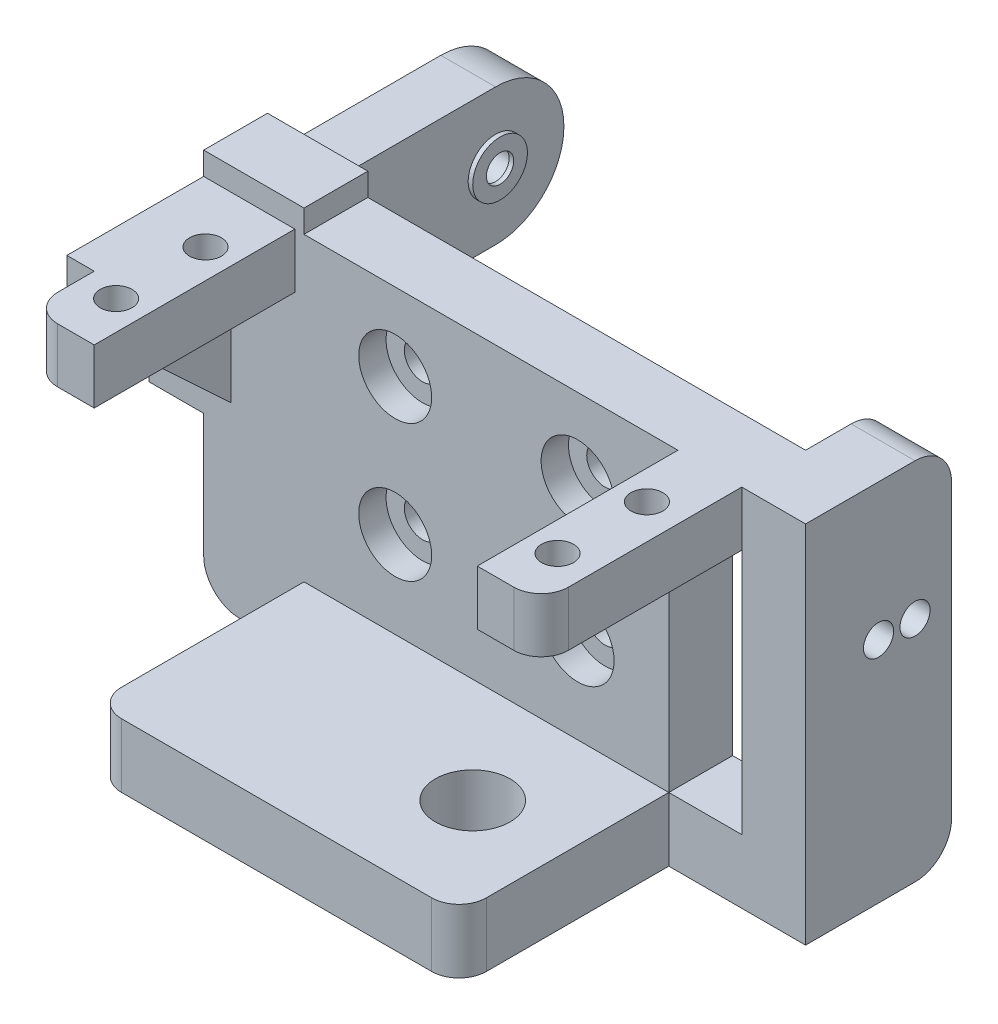
SolidWorks part; units mm, degrees
ref_plane "前视基准面" through (0, 0, 0) normal (0, 0, 1) x (1, 0, 0)
ref_plane "上视基准面" through (0, 0, 0) normal (0, 1, 0) x (1, 0, 0)
ref_plane "右视基准面" through (0, 0, 0) normal (1, 0, 0) x (0, 0, -1)
sketch "草图4" plane through (0, 0, 0) normal (0, 1, 0) x (1, 0, 0)
  line L0 (0, 17.6534) -> (0, -5.833) construction
  line L2 (-28, 28.5) -> (28, 28.5)
  line L3 (-28, 28.5) -> (-28, 2.5)
  line L4 (-25, -0.5) -> (-21, -0.5)
  line L5 (28, 28.5) -> (28, 2.5)
  line L6 (-28, 28.5) -> (28, -0.5) construction
  line L7 (-28, -0.5) -> (28, 28.5) construction
  line L8 (-21, 21.5) -> (21, 21.5)
  line L9 (-21, 21.5) -> (-21, -0.5)
  line L11 (21, 21.5) -> (21, -0.5)
  line L12 (-21, 21.5) -> (21, -0.5) construction
  line L13 (-21, -0.5) -> (21, 21.5) construction
  line L14 (21, -0.5) -> (25, -0.5)
  line L15 (20, 20) -> (-20, 20) construction
  circle A0 centre (-24.2, 14.9) radius 1.75
  circle A1 centre (-24.2, 5.1) radius 1.75
  circle A2 centre (24.2, 14.9) radius 1.75
  circle A3 centre (24.2, 5.1) radius 1.75
  arc A4 (25, -0.5) -> (28, 2.5) centre (25, 2.5) ccw
  arc A5 (-25, -0.5) -> (-28, 2.5) centre (-25, 2.5) cw
  point P3 (0, 14)
  point P8 (0, 10.5)
  dimension "D6" = 3.5
  dimension "D7" = 3.5
  dimension "D8" = 3.5
  dimension "D9" = 3.5
  dimension "D10" = 3
  dimension "D1" = 22
  dimension "D2" = 1.5
  dimension "D3" = 7
  dimension "D4" = 42
  dimension "D5" = 7
extrude "凸台-拉伸1" add sketch "草图4" against normal blind 6 from surface
sketch "草图5" plane through (0, 0, -28.5) normal (0, 0, -1) x (-1, 0, 0)
  line L0 (0, 4.5795) -> (0, 37.3232) construction
  line L1 (-28, 24.2) -> (28, 24.2) construction
  line L2 (-20, 24.2) -> (20, 24.2)
  line L3 (-20, 24.2) -> (-20, -9.8)
  line L4 (-20, -9.8) -> (20, -9.8)
  line L5 (20, 24.2) -> (20, -9.8)
  line L6 (-20, 24.2) -> (20, -9.8) construction
  line L7 (-20, -9.8) -> (20, 24.2) construction
  line L8 (-20, 14.2) -> (20, 14.2) construction
  circle A0 centre (-10, 21.7) radius 2
  circle A1 centre (10, 21.7) radius 2
  circle A4 centre (10, 6.7) radius 2
  circle A5 centre (-10, 6.7) radius 2
  point P3 (0, 7.2)
  dimension "D3" = 4
  dimension "D1" = 40
  dimension "D2" = 34
  dimension "D4" = 20
  dimension "D6" = 10
  dimension "D7" = 15
extrude "凸台-拉伸2" add sketch "草图5" against normal blind 7
sketch "草图6" plane through (0, 0, 0) normal (0, 0, 1) x (1, 0, 0)
  circle A0 centre (-10, 21.7) radius 4
  circle A1 centre (10, 21.7) radius 4
  circle A5 centre (-10, 6.7) radius 4
  circle A6 centre (10, 6.7) radius 4
  dimension "D1" = 8
extrude "切除-拉伸1" cut sketch "草图6" against normal blind 3 from surface at -21.5 starting at face at (0, 17.2, -21.5)
sketch "草图7" plane through (0, 0, 0) normal (0, 1, 0) x (1, 0, 0)
  line L0 (-20, 21.5) -> (-20, 28.5) construction
  line L1 (20, 21.5) -> (-20, 21.5)
  line L2 (20, 21.5) -> (20, 1.5)
  line L3 (17, -1.5) -> (-17, -1.5)
  line L4 (-20, 21.5) -> (-20, 1.5)
  circle A0 centre (10, 10) radius 4.1
  arc A1 (-17, -1.5) -> (-20, 1.5) centre (-17, 1.5) cw
  arc A2 (17, -1.5) -> (20, 1.5) centre (17, 1.5) ccw
  point P14 (20, -1.5)
  dimension "D1" = 8.2
  dimension "D3" = 3
  dimension "D2" = 23
extrude "凸台-拉伸3" add sketch "草图7" along normal blind 7 from surface at -9.8 starting at face at (0, -9.8, -25)
sketch "草图8" plane through (0, -9.8, 0) normal (0, -1, 0) x (1, 0, 0)
  circle A0 centre (10, -10) radius 4.9
  dimension "D1" = 9.8
extrude "切除-拉伸2" cut sketch "草图8" against normal blind 0.9
sketch "草图9" plane through (22, 25.2, -45.8683) normal (1, 0, 0) x (0, 0, 1)
  line L0 (30.2748, 10) -> (-26.3655, 10) construction
  line L1 (43.3683, 1) -> (17.3683, 1) construction
  line L2 (-7.6317, 2.5) -> (24.3683, 2.5)
  line L4 (-7.6317, 17.5) -> (24.3683, 17.5)
  line L5 (24.3683, 2.5) -> (24.3683, 17.5)
  line L6 (7.8683, 10) -> (24.3683, 17.5) construction
  line L7 (7.8683, 10) -> (24.3683, 2.5) construction
  line L9 (24.3683, 1) -> (24.3683, 28) construction
  circle A0 centre (-7.6317, 10) radius 1.65
  arc A1 (-7.6317, 17.5) -> (-7.6317, 2.5) centre (-7.6317, 10) ccw
  point P5 (7.8683, 10)
  dimension "D1" = 3.3
  dimension "D3" = 7.5
  dimension "D2" = 15
  dimension "D4" = 32
  dimension "D5" = 9
extrude "凸台-拉伸4" add sketch "草图9" against normal blind 6 from offset 53 separate body offset against normal yes
sketch "草图10" plane through (0, 0, 0) normal (0, 0, 1) x (1, 0, 0)
  line L10 (-31, 32.7) -> (-20, 32.7)
  line L11 (-20, 32.7) -> (-20, -9.8)
  line L14 (-31, 32.7) -> (-31, -5.8)
  line L15 (-31, 22.7) -> (-31, 7.7) construction
  line L16 (-27, -9.8) -> (-20, -9.8)
  line L17 (-20, -9.8) -> (-17, -9.8) construction
  arc A1 (-31, -5.8) -> (-27, -9.8) centre (-27, -5.8) ccw
  dimension "D1" = 4
extrude "凸台-拉伸5" add sketch "草图10" against normal blind 7 from surface at -21.5 starting at face at (-34, 15.2, -21.5)
sketch "草图12" plane through (0, 0, 0) normal (1, 0, 0) x (0, 0, -1)
  line L0 (6.5, 30.2) -> (6.5, 24.2)
  line L1 (21.5, 30.2) -> (2.5, 30.2) construction
  line L2 (21.5, 24.2) -> (2.5, 24.2) construction
  line L3 (6.5, 30.2) -> (21.5, 30.2)
  line L7 (21.5, 30.2) -> (21.5, 10.2)
  line L8 (21.5, 24.2) -> (21.5, -2.8) construction
  line L9 (21.5, 10.2) -> (6.5, 24.2)
  dimension "D1" = 15
  dimension "D2" = 20
extrude "凸台-拉伸7" add sketch "草图12" against normal up to surface (3 mm away) from surface at -28 up to face at (-31, 27.7, -25) starting at face at (-28, 27.2, -12)
sketch "草图14" plane through (0, 0, 0) normal (1, 0, 0) x (0, 0, -1)
  line L0 (2.5, 30.2) -> (28.5, 30.2) construction
  line L6 (21.5, 30.2) -> (33.5, 30.2)
  line L7 (21.5, 30.2) -> (21.5, -9.8)
  line L8 (21.5, -9.8) -> (33.5, -9.8)
  line L9 (37.5, 26.2) -> (37.5, -5.8)
  line L10 (1.5, -9.8) -> (28.5, -9.8) construction
  line L11 (21.5, 15.2) -> (37.5, 15.2) construction
  circle A0 centre (29.5, 15.2) radius 1.65
  circle A1 centre (33.5, 15.2) radius 1.65
  arc A2 (37.5, 26.2) -> (33.5, 30.2) centre (33.5, 26.2) ccw
  arc A3 (33.5, -9.8) -> (37.5, -5.8) centre (33.5, -5.8) ccw
  dimension "D3" = 3.3
  dimension "D4" = 3.3
  dimension "D5" = 4
  dimension "D6" = 4
  dimension "D1" = 8
  dimension "D2" = 4
  dimension "D7" = 4
  dimension "D8" = 37.5
  dimension "D9" = 15
extrude "凸台-拉伸8" add sketch "草图14" along normal blind 7 from surface at 28 starting at face at (28, 27.2, -15.5)
sketch "草图15" plane through (0, 0, 0) normal (0, 1, 0) x (1, 0, 0)
  line L0 (-21, 21.5) -> (-31, 21.5) construction
  line L1 (28, 21.5) -> (20, 21.5)
  line L2 (28, 21.5) -> (28, 28.5)
  line L3 (28, 28.5) -> (20, 28.5)
  line L4 (20, 21.5) -> (20, 28.5)
  line L5 (28, 2.5) -> (28, 21.5) construction
extrude "凸台-拉伸9" add sketch "草图15" along normal blind 7 from surface at -9.8 starting at face at (10, -9.8, -14.9)
sketch "草图17" plane through (-31, 0, 0) normal (1, 0, 0) x (0, 0, -1)
  circle A0 centre (53.5, 15.2) radius 3
  circle A1 centre (53.5, 15.2) radius 1.5
  dimension "D1" = 6
extrude "凸台-拉伸11" add sketch "草图17" along normal blind 0.5
